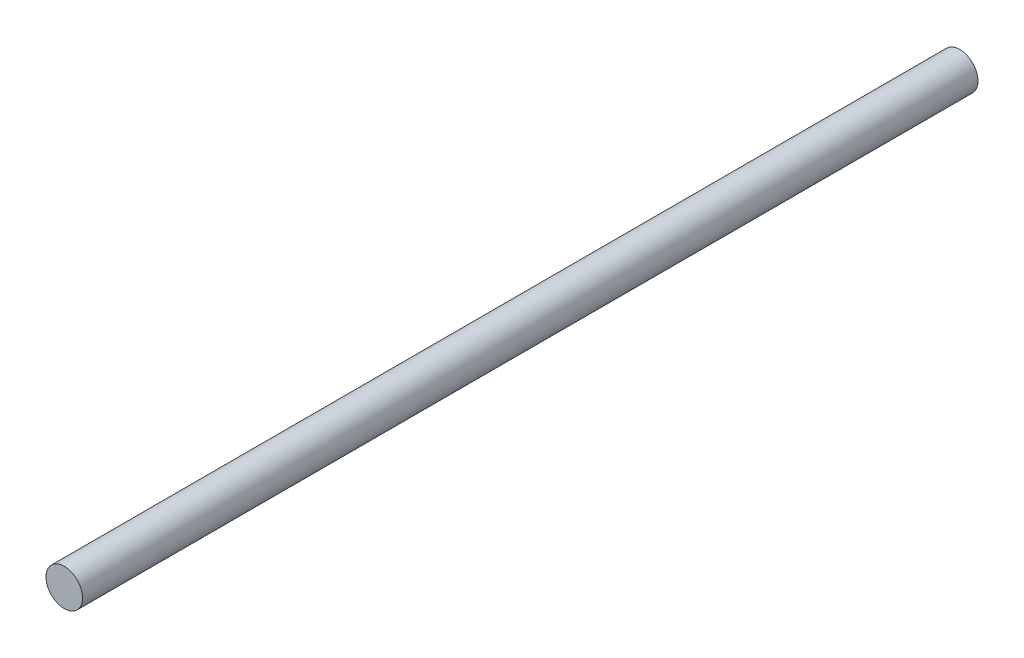
SolidWorks part; units mm, degrees
ref_plane "Front Plane" through (0, 0, 0) normal (0, 0, 1) x (1, 0, 0)
ref_plane "Top Plane" through (0, 0, 0) normal (0, 1, 0) x (1, 0, 0)
ref_plane "Right Plane" through (0, 0, 0) normal (1, 0, 0) x (0, 0, -1)
sketch "Sketch1" plane through (0, 0, 0) normal (0, 0, 1) x (1, 0, 0)
  circle A0 centre (0, 0) radius 6.75
  dimension "D1" = 13.5
extrude "Boss-Extrude1" add sketch "Sketch1" along normal blind 330
